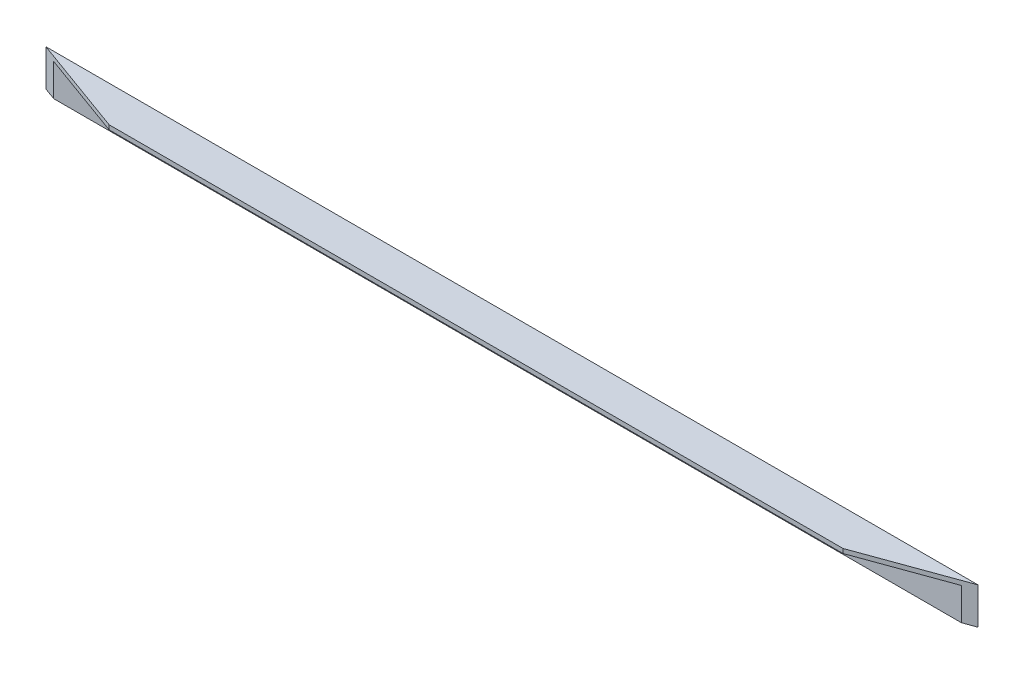
SolidWorks part; units mm, degrees
ref_plane "前视" through (0, 0, 0) normal (0, 0, 1) x (1, 0, 0)
ref_plane "上视" through (0, 0, 0) normal (0, 1, 0) x (1, 0, 0)
ref_plane "右视" through (0, 0, 0) normal (1, 0, 0) x (0, 0, -1)
sketch "草图1" plane through (0, 0, 0) normal (0, 0, 1) x (1, 0, 0)
  line L0 (-514.4277, 0) -> (1448.6337, 0) construction
  line L1 (-1270, 50) -> (1270, 50)
  line L2 (-1270, 50) -> (-1270, -50)
  line L3 (-1270, -50) -> (1270, -50)
  line L4 (1270, 50) -> (1270, -50)
  line L5 (0, 212.5086) -> (0, -250.4285) construction
  dimension "D1" = 50
  dimension "D2" = 2540
extrude "基体-拉伸" add sketch "草图1" along normal blind 12
sketch "草图2" plane through (0, 0, 12) normal (0, 0, 1) x (1, 0, 0)
  line L1 (-1270, 50) -> (1270, 50)
  line L2 (-1270, 50) -> (-1270, 38)
  line L3 (-1270, 38) -> (1270, 38)
  line L4 (1270, 50) -> (1270, 38)
  dimension "D1" = 12
extrude "凸台-拉伸1" add sketch "草图2" along normal blind 86
sketch "草图4" plane through (0, 50, 0) normal (0, 1, 0) x (-1, 0, 0)
  line L0 (-1270, 0) -> (-1270, 98)
  line L3 (-1270, 98) -> (-1000, 98)
  line L4 (-1270, 98) -> (1270, 98) construction
  line L5 (-1270, 0) -> (-1000, 98)
  line L6 (0, 322.0836) -> (0, -403.7798) construction
  line L7 (1270, 0) -> (1000, 98)
  line L8 (1270, 98) -> (1000, 98)
  line L9 (1270, 0) -> (1270, 98)
  dimension "D1" = 270
extrude "切除-拉伸1" cut sketch "草图4" against normal through all
